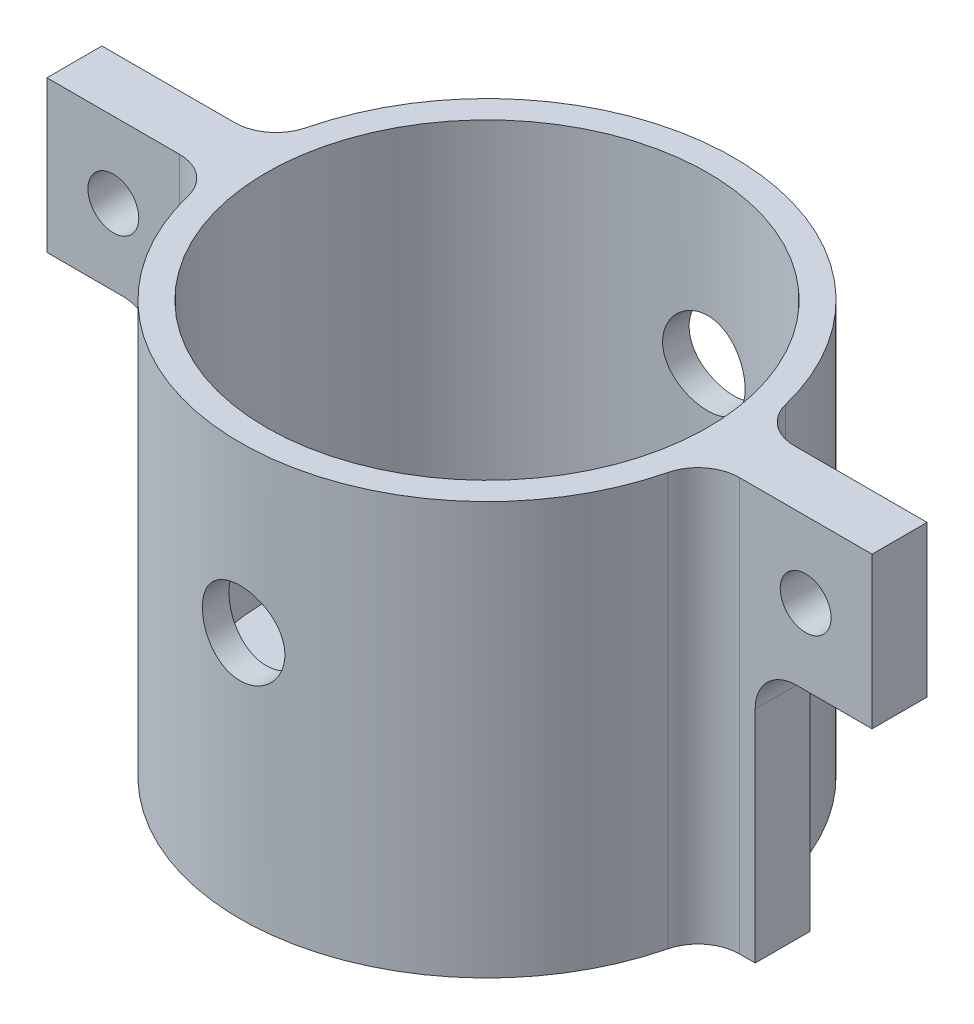
SolidWorks part; units mm, degrees
ref_plane "Front Plane" through (0, 0, 0) normal (0, 0, 1) x (1, 0, 0)
ref_plane "Top Plane" through (0, 0, 0) normal (0, 1, 0) x (1, 0, 0)
ref_plane "Right Plane" through (0, 0, 0) normal (1, 0, 0) x (0, 0, -1)
sketch "Sketch1" plane through (0, 0, 0) normal (0, 1, 0) x (1, 0, 0)
  line L5 (-31.3914, 0) -> (30.2135, 0) construction
  line L6 (-30, -2) -> (-30, 2)
  line L7 (-30, 2) -> (-17.8382, 2)
  line L8 (0, 28.1368) -> (0, -32.1926) construction
  line L9 (30, -2) -> (30, 2)
  line L10 (30, 2) -> (17.8382, 2)
  line L11 (-30, -2) -> (-17.8382, -2)
  line L12 (30, -2) -> (17.8382, -2)
  arc A4 (-17.8382, 2) -> (17.8382, 2) centre (0, 0) cw
  arc A5 (17.8382, -2) -> (-17.8382, -2) centre (0, 0) cw
  point P14 (-30, 0)
  point P16 (30, 0)
  dimension "D1" = 17.95
  dimension "D4" = 4
  dimension "D2" = 17.95
  dimension "D3" = 60
extrude "Boss-Extrude1" add sketch "Sketch1" along normal blind 30
sketch "Sketch4" plane through (-30, 0, 0) normal (-1, 0, 0) x (0, 0, 1)
  line L0 (2, 30) -> (2, 0) construction
  line L1 (-2, 0) -> (2, 0)
  line L2 (-2, 0) -> (-2, 19)
  line L3 (-2, 19) -> (2, 19)
  line L4 (2, 0) -> (2, 19)
  dimension "D1" = 19
extrude "Cut-Extrude3" cut sketch "Sketch4" against normal blind 8.5
ref_plane "Plane1" through (0, 0, 0) normal (1, 0, 0) x (0, 0, -1)
mirror "Mirror1" about plane through (0, 0, 0) normal (1, 0, 0) of "Cut-Extrude3"
sketch "Sketch6" plane through (0, 0, 0) normal (0, -1, 0) x (1, 0, 0)
  circle A0 centre (0, 0) radius 9
sketch "Sketch7" plane through (0, 30, 0) normal (0, 1, 0) x (1, 0, 0)
  circle A0 centre (0, 0) radius 16.05
  dimension "D1" = 32.1
extrude "Cut-Extrude4" cut sketch "Sketch7" against normal blind 27
extrude "Cut-Extrude5" cut sketch "Sketch6" against normal blind 4
fillet "Fillet3" radius 3 4 edges at (17.8382, 15, 2) (17.8382, 15, -2) (-17.8382, 15, 2) (-17.8382, 15, -2)
fillet "Fillet4" radius 3 2 edges at (-21.5, 19, 0) (21.5, 19, 0)
sketch "Sketch8" plane through (0, 0, -2) normal (0, 0, -1) x (-1, 0, 0)
  line L0 (-25.17, 25.48) -> (-25.17, 9.6984) construction
  line L1 (-30.8488, 24.5) -> (-19.4912, 24.5) construction
  line L2 (0, 40.2686) -> (0, -8.7145) construction
  line L3 (0, 2.2) -> (0, -2.2) construction
  line L4 (30.8488, 24.5) -> (19.4912, 24.5) construction
  line L5 (25.17, 25.48) -> (25.17, 9.6984) construction
  line L7 (-30, 30) -> (-20.3446, 30) construction
  line L10 (30, 30) -> (30, 19) construction
  circle A0 centre (-25.17, 24.5) radius 1.85
  circle A1 centre (25.17, 24.5) radius 1.85
  dimension "D1" = 5.5
  dimension "D4" = 3.7
  dimension "D2" = 4.83
  dimension "D3" = 0
extrude "Cut-Extrude6" cut sketch "Sketch8" against normal blind 4
ref_plane "Plane2" through (0, 0, -17.95) normal (0, 0, -1) x (-1, 0, 0)
sketch "Sketch9" plane through (0, 0, -17.95) normal (0, 0, -1) x (-1, 0, 0)
  line L0 (0, 30) -> (0, -9.7101) construction
  line L1 (17.4313, 30) -> (-17.4313, 30) construction
  line L2 (0, 2.2) -> (0, -2.2) construction
  line L3 (-32.3782, 18) -> (35.4769, 18) construction
  line L4 (-17.4313, 0) -> (17.4313, 0) construction
  circle A0 centre (0, 18) radius 3
  dimension "D1" = 18
extrude "Cut-Extrude7" cut sketch "Sketch9" against normal blind 37
equation "\"5.5.00mm\"=5"
